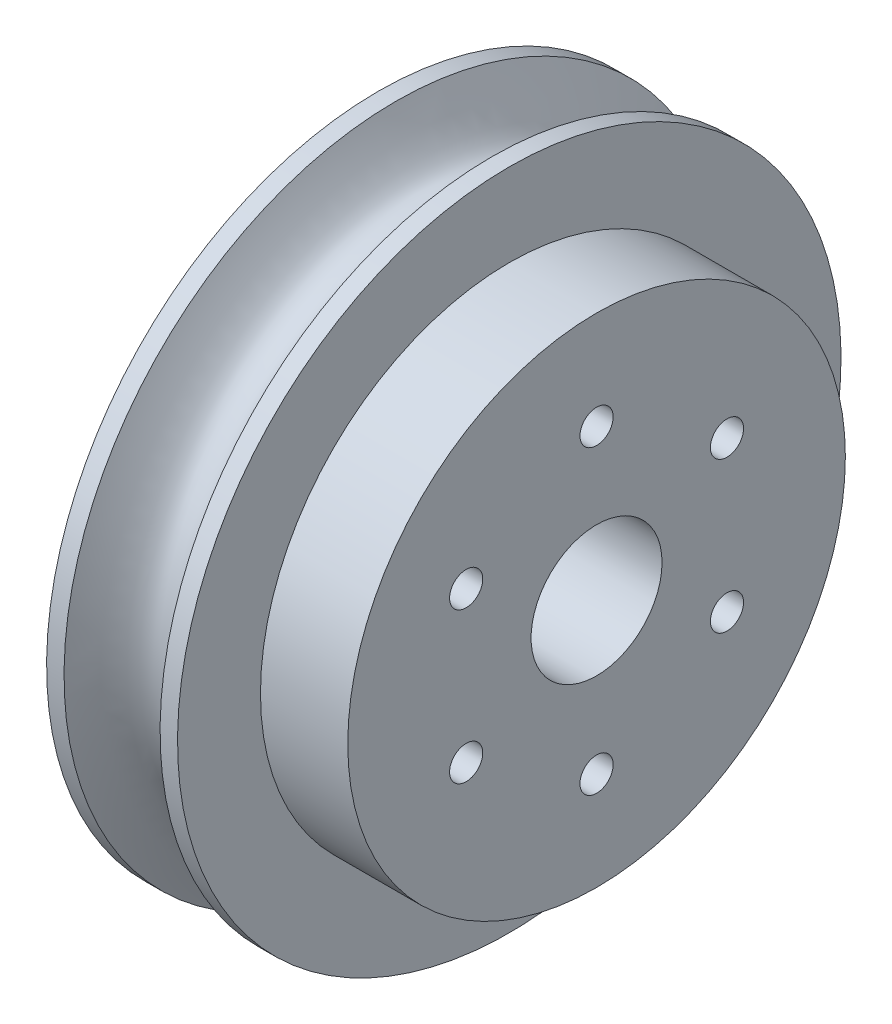
SolidWorks part; units mm, degrees
ref_plane "前视基准面" through (0, 0, 0) normal (0, 0, 1) x (1, 0, 0)
ref_plane "上视基准面" through (0, 0, 0) normal (0, 1, 0) x (1, 0, 0)
ref_plane "右视基准面" through (0, 0, 0) normal (1, 0, 0) x (0, 0, -1)
sketch "草图1" plane through (0, 0, 0) normal (1, 0, 0) x (0, 0, -1)
  circle A0 centre (0, 0) radius 17.25 construction
  circle A1 centre (0, 17.25) radius 1.9
  circle A2 centre (14.9389, 8.625) radius 1.9
  circle A3 centre (14.9389, -8.625) radius 1.9
  circle A4 centre (0, -17.25) radius 1.9
  circle A5 centre (-14.9389, -8.625) radius 1.9
  circle A6 centre (-14.9389, 8.625) radius 1.9
  circle A7 centre (0, 0) radius 28.5
  circle A8 centre (0, 0) radius 7.5
  dimension "D1" = 34.5
  dimension "D2" = 3.8
  dimension "D4" = 57
  dimension "D5" = 15
  dimension "D3" = 6
extrude "凸台-拉伸1" add sketch "草图1" along normal blind 10
sketch "Sketch2" plane through (0, 0, 0) normal (0, 0, 1) x (1, 0, 0)
  line L0 (0, 0) -> (-15, 0)
  line L1 (-2, 38) -> (0, 38)
  line L2 (-15, 38) -> (-15, 0)
  line L3 (0, 38) -> (0, 0)
  line L6 (-15, 38) -> (-13, 38)
  line L7 (-7.5, 0) -> (-7.5, 21.5484) construction
  spline S0 degree 3 poles (-13, 38) (-9.9771, 32.0396) (-7.5155, 32.0193) (-5.0031, 32.0529) (-2, 38) knots 0.048052 0.048052 0.048052 0.048052 0.500505 0.951948 0.951948 0.951948 0.951948
  point P8 (-12, 24.8519)
  point P10 (-9, 23.9701)
  point P12 (-9, 28.6589)
  point P13 (-7.5, 28.5011)
  point P14 (-7.1253, 31.9466)
  point P15 (-7.5, 32.0328)
  dimension "D1" = 38
  dimension "D2" = 15
  dimension "D3" = 2
  dimension "D4" = 2
  dimension "D5" = 38
revolve "Revolve1" add sketch "Sketch2" angle 360 about L0
sketch "Sketch3" plane through (10, 0, 0) normal (1, 0, 0) x (0, 0, -1)
  circle A0 centre (14.9389, 8.625) radius 1.9 construction
  circle A1 centre (14.9389, -8.625) radius 1.9 construction
  circle A2 centre (0, -17.25) radius 1.9 construction
  circle A3 centre (-14.9389, -8.625) radius 1.9 construction
  circle A4 centre (0, 17.25) radius 1.9 construction
  circle A5 centre (-14.9389, 8.625) radius 1.9 construction
  circle A6 centre (14.9389, 8.625) radius 1.9
  circle A7 centre (14.9389, -8.625) radius 1.9
  circle A8 centre (0, -17.25) radius 1.9
  circle A9 centre (-14.9389, -8.625) radius 1.9
  circle A10 centre (0, 17.25) radius 1.9
  circle A11 centre (-14.9389, 8.625) radius 1.9
  circle A12 centre (0, 0) radius 7.5 construction
  circle A13 centre (0, 0) radius 7.5
extrude "Cut-Extrude1" cut sketch "Sketch3" against normal through all
sketch "Sketch4" plane through (-15, 0, 0) normal (-1, 0, 0) x (0, 0, 1)
  circle A1 centre (-14.9389, -8.625) radius 1.9 construction
  circle A2 centre (0, -17.25) radius 1.9 construction
  circle A3 centre (14.9389, -8.625) radius 1.9 construction
  circle A4 centre (14.9389, 8.625) radius 1.9 construction
  circle A7 centre (-14.9389, -8.625) radius 1.9 construction
  circle A8 centre (0, -17.25) radius 1.9 construction
  circle A9 centre (14.9389, -8.625) radius 1.9 construction
  circle A10 centre (14.9389, 8.625) radius 1.9 construction
  circle A13 centre (14.9389, 8.625) radius 4
  circle A15 centre (14.9389, -8.625) radius 4
  circle A16 centre (0, -17.25) radius 4
  circle A17 centre (-14.9389, -8.625) radius 4
  circle A18 centre (-14.9389, 8.625) radius 4
  circle A19 centre (0, 17.25) radius 4
  point P25 (0, 0)
  dimension "D1" = 8
  dimension "D2" = 6
extrude "Cut-Extrude2" cut sketch "Sketch4" against normal blind 5
